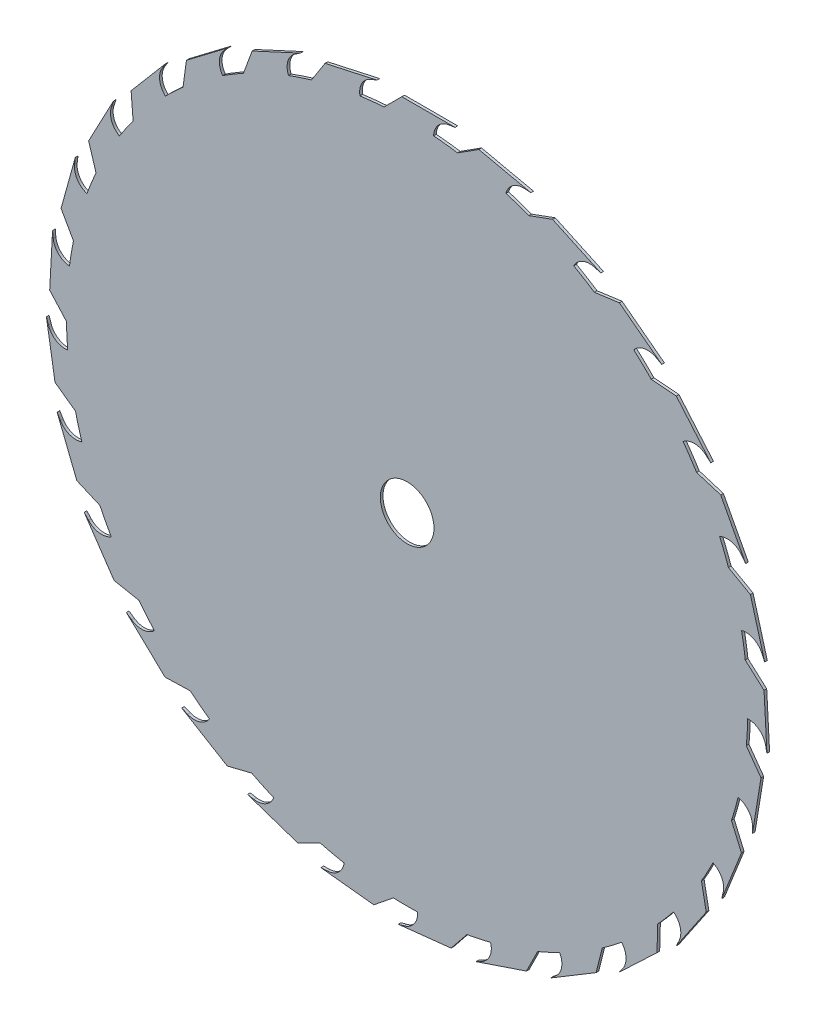
SolidWorks part; units mm, degrees
ref_plane "Front Plane" through (0, 0, 0) normal (0, 0, 1) x (1, 0, 0)
ref_plane "Top Plane" through (0, 0, 0) normal (0, 1, 0) x (1, 0, 0)
ref_plane "Right Plane" through (0, 0, 0) normal (1, 0, 0) x (0, 0, -1)
sketch "Sketch1" plane through (0, 0, 0) normal (0, 0, 1) x (1, 0, 0)
  circle A0 centre (0, 0) radius 203.2
  dimension "D1" = 406.4
extrude "Boss-Extrude1" add sketch "Sketch1" along normal blind 1.5875 contours A0
sketch "Sketch2" plane through (0, 0, 1.5875) normal (0, 0, 1) x (1, 0, 0)
  circle A0 centre (0, 0) radius 16.002
  dimension "D1" = 32.004
extrude "Cut-Extrude1" cut sketch "Sketch2" against normal up to next
sketch "Sketch4" plane through (0, 0, 1.5875) normal (0, 0, 1) x (1, 0, 0)
  line L0 (-15.875, 200.66) -> (-3.175, 213.36)
  line L1 (-3.175, 213.36) -> (28.575, 213.36)
  line L2 (28.575, 213.36) -> (24.8089, 212.7835)
  line L3 (15.875, 200.66) -> (-15.875, 200.66)
  arc A0 (24.8089, 212.7835) -> (15.875, 200.66) centre (26.4227, 202.2408) ccw
  point P8 (0, 200.66)
  dimension "D1" = 3.81
  dimension "D7" = 1.5808
  dimension "D2" = 31.75
  dimension "D3" = 12.7
  dimension "D4" = 31.75
  dimension "D5" = 213.36
  dimension "D6" = 45
extrude "Boss-Extrude2" add sketch "Sketch4" against normal up to surface (1.5875 mm away) up to face at (16.002, 0, 0)
pattern_circular "CirPattern1" count 29 over 360 about axis through (0, 0, 0) along (0, 0, 1) of "Boss-Extrude2"
